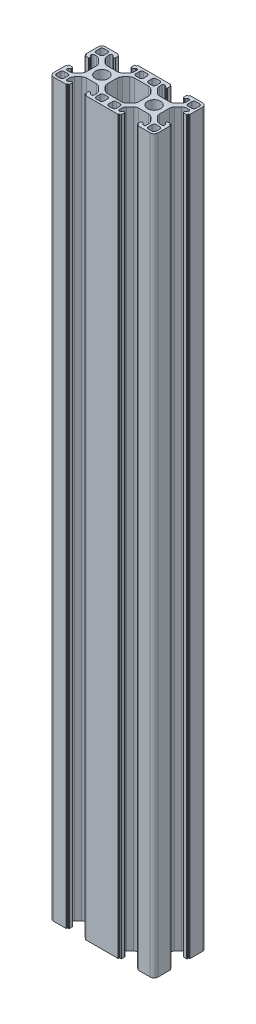
SolidWorks part; units mm, degrees
ref_plane "Спереди" through (0, 0, 0) normal (0, 0, 1) x (1, 0, 0)
ref_plane "Сверху" through (0, 0, 0) normal (0, 1, 0) x (1, 0, 0)
ref_plane "Справа" through (0, 0, 0) normal (1, 0, 0) x (0, 0, -1)
sketch "Эскиз1" plane through (0, 0, 0) normal (0, 1, 0) x (1, 0, 0)
  line L0 (-3.1522, 8.2837) -> (-1.6522, 6.7837) construction
  line L1 (18.3478, 9.7837) -> (15.3478, 6.7837) construction
  line L2 (-10.7522, 0.6837) -> (-0.7522, 10.6837) construction
  line L3 (9.2478, 4.6837) -> (11.1466, 4.6837)
  line L4 (9.2478, 0.6837) -> (19.2478, 10.6837) construction
  line L5 (16.8478, 8.2837) -> (15.3478, 9.7837) construction
  line L6 (12.5608, 5.2695) -> (13.862, 6.5707)
  line L7 (16.1478, 6.7837) -> (17.5478, 6.7837)
  line L8 (15.3478, 7.5837) -> (15.3478, 8.9837)
  line L9 (17.5478, 9.7837) -> (16.1478, 9.7837)
  line L10 (14.4478, 8.8837) -> (14.4478, 7.9849)
  line L11 (13.011, 8.757) -> (13.4914, 9.2373)
  line L12 (12.4478, 10.2328) -> (12.9478, 10.2328)
  line L13 (12.8343, 8.6837) -> (12.5478, 8.6837)
  line L14 (13.8449, 9.3837) -> (13.9478, 9.3837)
  line L15 (12.9478, 10.5337) -> (12.9478, 10.2328)
  line L16 (12.2978, 10.0828) -> (12.2978, 8.9337)
  line L17 (17.7478, 10.6837) -> (13.0978, 10.6837)
  line L18 (18.3478, 8.9837) -> (18.3478, 7.5837)
  line L19 (19.2478, 9.1837) -> (19.2478, 4.5337)
  line L20 (18.6469, 3.7337) -> (17.4978, 3.7337)
  line L21 (19.0978, 4.3837) -> (18.7969, 4.3837)
  line L22 (17.9478, 5.2808) -> (17.9478, 5.3837)
  line L23 (17.2478, 4.2702) -> (17.2478, 3.9837)
  line L24 (18.7969, 3.8837) -> (18.7969, 4.3837)
  line L25 (17.321, 4.447) -> (17.8014, 4.9273)
  line L26 (17.4478, 5.8837) -> (16.549, 5.8837)
  line L27 (13.8336, 3.9967) -> (15.1348, 5.2979)
  line L28 (13.2478, 0.6837) -> (13.2478, 2.5825)
  line L29 (13.2478, 0.6837) -> (13.2478, -1.2151)
  line L30 (13.8336, -2.6293) -> (15.1348, -3.9305)
  line L31 (15.3478, -6.2163) -> (15.3478, -7.6163)
  line L32 (16.1478, -5.4163) -> (17.5478, -5.4163)
  line L33 (18.3478, -7.6163) -> (18.3478, -6.2163)
  line L34 (17.4478, -4.5163) -> (16.549, -4.5163)
  line L35 (17.321, -3.0795) -> (17.8014, -3.5598)
  line L36 (18.7969, -2.5163) -> (18.7969, -3.0163)
  line L37 (17.2478, -2.9027) -> (17.2478, -2.6163)
  line L38 (17.9478, -3.9134) -> (17.9478, -4.0163)
  line L39 (19.0978, -3.0163) -> (18.7969, -3.0163)
  line L40 (18.6469, -2.3663) -> (17.4978, -2.3663)
  line L41 (19.2478, -7.8163) -> (19.2478, -3.1663)
  line L42 (17.5478, -8.4163) -> (16.1478, -8.4163)
  line L43 (17.7478, -9.3163) -> (13.0978, -9.3163)
  line L44 (12.2978, -8.7153) -> (12.2978, -7.5663)
  line L45 (12.9478, -9.1663) -> (12.9478, -8.8653)
  line L46 (13.8449, -8.0163) -> (13.9478, -8.0163)
  line L47 (12.8343, -7.3163) -> (12.5478, -7.3163)
  line L48 (12.4478, -8.8653) -> (12.9478, -8.8653)
  line L49 (13.011, -7.3895) -> (13.4914, -7.8698)
  line L50 (14.4478, -7.5163) -> (14.4478, -6.6175)
  line L51 (12.5608, -3.9021) -> (13.862, -5.2033)
  line L52 (9.2478, -3.3163) -> (11.1466, -3.3163)
  line L53 (18.3478, -8.4163) -> (15.3478, -5.4163) construction
  line L54 (9.2478, 0.6837) -> (19.2478, -9.3163) construction
  line L55 (16.8478, -6.9163) -> (18.3478, -5.4163) construction
  line L56 (9.2478, -3.3163) -> (7.349, -3.3163)
  line L57 (5.9348, -3.9021) -> (4.6336, -5.2033)
  line L58 (2.3478, -5.4163) -> (0.9478, -5.4163)
  line L59 (3.1478, -6.2163) -> (3.1478, -7.6163)
  line L60 (0.9478, -8.4163) -> (2.3478, -8.4163)
  line L61 (4.0478, -7.5163) -> (4.0478, -6.6175)
  line L62 (5.4846, -7.3895) -> (5.0043, -7.8698)
  line L63 (6.0478, -8.8653) -> (5.5478, -8.8653)
  line L64 (5.6614, -7.3163) -> (5.9478, -7.3163)
  line L65 (4.6507, -8.0163) -> (4.5478, -8.0163)
  line L66 (5.5478, -9.1663) -> (5.5478, -8.8653)
  line L67 (6.1978, -8.7153) -> (6.1978, -7.5663)
  line L68 (0.7478, -9.3163) -> (5.3978, -9.3163)
  line L69 (0.1478, -7.6163) -> (0.1478, -6.2163)
  line L70 (1.0478, -4.5163) -> (1.9466, -4.5163)
  line L71 (4.662, -2.6293) -> (3.3608, -3.9305)
  line L72 (5.2478, 0.6837) -> (5.2478, -1.2151)
  line L73 (-1.6522, 9.7837) -> (-4.6522, 6.7837) construction
  line L74 (0.1478, -8.4163) -> (3.1478, -5.4163) construction
  line L75 (-3.1522, -6.9163) -> (-4.6522, -8.4163) construction
  line L76 (9.2478, 0.6837) -> (-0.7522, -9.3163) construction
  line L77 (1.6478, -6.9163) -> (3.1478, -8.4163) construction
  line L78 (5.2478, 0.6837) -> (5.2478, 2.5825)
  line L79 (4.662, 3.9967) -> (3.3608, 5.2979)
  line L80 (3.1478, 7.5837) -> (3.1478, 8.9837)
  line L81 (2.3478, 6.7837) -> (0.9478, 6.7837)
  line L82 (0.1478, 8.9837) -> (0.1478, 7.5837)
  line L83 (1.0478, 5.8837) -> (1.9466, 5.8837)
  line L84 (0.9478, 9.7837) -> (2.3478, 9.7837)
  line L85 (0.7478, 10.6837) -> (5.3978, 10.6837)
  line L86 (6.1978, 10.0828) -> (6.1978, 8.9337)
  line L87 (5.5478, 10.5337) -> (5.5478, 10.2328)
  line L88 (4.6507, 9.3837) -> (4.5478, 9.3837)
  line L89 (5.6614, 8.6837) -> (5.9478, 8.6837)
  line L90 (6.0478, 10.2328) -> (5.5478, 10.2328)
  line L91 (5.4846, 8.757) -> (5.0043, 9.2373)
  line L92 (4.0478, 8.8837) -> (4.0478, 7.9849)
  line L93 (5.9348, 5.2695) -> (4.6336, 6.5707)
  line L94 (9.2478, 4.6837) -> (7.349, 4.6837)
  line L95 (-2.5162, 0.6837) -> (20.7522, 0.6837) construction
  line L96 (0.1478, 9.7837) -> (3.1478, 6.7837) construction
  line L97 (9.2478, -11.4027) -> (9.2478, 11.4027) construction
  line L98 (9.2478, 0.6837) -> (-0.7522, 10.6837) construction
  line L99 (1.6478, 8.2837) -> (0.1478, 6.7837) construction
  line L100 (-10.7522, 0.6837) -> (-0.7522, -9.3163) construction
  line L101 (-1.6522, -8.4163) -> (-4.6522, -5.4163) construction
  line L102 (-18.3522, -6.9163) -> (-19.8522, -5.4163) construction
  line L103 (-10.7522, 0.6837) -> (-20.7522, -9.3163) construction
  line L104 (-19.8522, -8.4163) -> (-16.8522, -5.4163) construction
  line L105 (-18.3522, 8.2837) -> (-16.8522, 9.7837) construction
  line L106 (-10.7522, 0.6837) -> (-20.7522, 10.6837) construction
  line L107 (-19.8522, 9.7837) -> (-16.8522, 6.7837) construction
  line L108 (-10.7522, 4.6837) -> (-8.8534, 4.6837)
  line L109 (-7.4392, 5.2695) -> (-6.138, 6.5707)
  line L110 (-5.5522, 8.8837) -> (-5.5522, 7.9849)
  line L111 (-6.989, 8.757) -> (-6.5086, 9.2373)
  line L112 (-7.5522, 10.2328) -> (-7.0522, 10.2328)
  line L113 (-7.1657, 8.6837) -> (-7.4522, 8.6837)
  line L114 (-6.1551, 9.3837) -> (-6.0522, 9.3837)
  line L115 (-7.0522, 10.5337) -> (-7.0522, 10.2328)
  line L116 (-7.7022, 10.0828) -> (-7.7022, 8.9337)
  line L117 (-2.2522, 10.6837) -> (-6.9022, 10.6837)
  line L118 (-2.4522, 9.7837) -> (-3.8522, 9.7837)
  line L119 (-2.5522, 5.8837) -> (-3.451, 5.8837)
  line L120 (-1.6522, 8.9837) -> (-1.6522, 7.5837)
  line L121 (-3.8522, 6.7837) -> (-2.4522, 6.7837)
  line L122 (-4.6522, 7.5837) -> (-4.6522, 8.9837)
  line L123 (-6.1664, 3.9967) -> (-4.8652, 5.2979)
  line L124 (-6.7522, 0.6837) -> (-6.7522, 2.5825)
  line L125 (-6.7522, 0.6837) -> (-6.7522, -1.2151)
  line L126 (-6.1664, -2.6293) -> (-4.8652, -3.9305)
  line L127 (-2.5522, -4.5163) -> (-3.451, -4.5163)
  line L128 (-1.6522, -7.6163) -> (-1.6522, -6.2163)
  line L129 (-2.2522, -9.3163) -> (-6.9022, -9.3163)
  line L130 (-7.7022, -8.7153) -> (-7.7022, -7.5663)
  line L131 (-7.0522, -9.1663) -> (-7.0522, -8.8653)
  line L132 (-6.1551, -8.0163) -> (-6.0522, -8.0163)
  line L133 (-7.1657, -7.3163) -> (-7.4522, -7.3163)
  line L134 (-7.5522, -8.8653) -> (-7.0522, -8.8653)
  line L135 (-6.989, -7.3895) -> (-6.5086, -7.8698)
  line L136 (-5.5522, -7.5163) -> (-5.5522, -6.6175)
  line L137 (-2.4522, -8.4163) -> (-3.8522, -8.4163)
  line L138 (-4.6522, -6.2163) -> (-4.6522, -7.6163)
  line L139 (-3.8522, -5.4163) -> (-2.4522, -5.4163)
  line L140 (-7.4392, -3.9021) -> (-6.138, -5.2033)
  line L141 (-10.7522, -3.3163) -> (-8.8534, -3.3163)
  line L142 (-10.7522, -3.3163) -> (-12.651, -3.3163)
  line L143 (-14.0652, -3.9021) -> (-15.3664, -5.2033)
  line L144 (-15.9522, -7.5163) -> (-15.9522, -6.6175)
  line L145 (-14.5154, -7.3895) -> (-14.9957, -7.8698)
  line L146 (-13.9522, -8.8653) -> (-14.4522, -8.8653)
  line L147 (-14.3386, -7.3163) -> (-14.0522, -7.3163)
  line L148 (-15.3493, -8.0163) -> (-15.4522, -8.0163)
  line L149 (-14.4522, -9.1663) -> (-14.4522, -8.8653)
  line L150 (-13.8022, -8.7153) -> (-13.8022, -7.5663)
  line L151 (-19.2522, -9.3163) -> (-14.6022, -9.3163)
  line L152 (-19.0522, -8.4163) -> (-17.6522, -8.4163)
  line L153 (-20.7522, -7.8163) -> (-20.7522, -3.1663)
  line L154 (-20.1512, -2.3663) -> (-19.0022, -2.3663)
  line L155 (-20.6022, -3.0163) -> (-20.3012, -3.0163)
  line L156 (-19.4522, -3.9134) -> (-19.4522, -4.0163)
  line L157 (-18.7522, -2.9027) -> (-18.7522, -2.6163)
  line L158 (-20.3012, -2.5163) -> (-20.3012, -3.0163)
  line L159 (-18.8254, -3.0795) -> (-19.3057, -3.5598)
  line L160 (-18.9522, -4.5163) -> (-18.0534, -4.5163)
  line L161 (-19.8522, -7.6163) -> (-19.8522, -6.2163)
  line L162 (-17.6522, -5.4163) -> (-19.0522, -5.4163)
  line L163 (-16.8522, -6.2163) -> (-16.8522, -7.6163)
  line L164 (-15.338, -2.6293) -> (-16.6392, -3.9305)
  line L165 (-14.7522, 0.6837) -> (-14.7522, -1.2151)
  line L166 (-14.7522, 0.6837) -> (-14.7522, 2.5825)
  line L167 (-15.338, 3.9967) -> (-16.6392, 5.2979)
  line L168 (-18.9522, 5.8837) -> (-18.0534, 5.8837)
  line L169 (-18.8254, 4.447) -> (-19.3057, 4.9273)
  line L170 (-20.3012, 3.8837) -> (-20.3012, 4.3837)
  line L171 (-18.7522, 4.2702) -> (-18.7522, 3.9837)
  line L172 (-19.4522, 5.2808) -> (-19.4522, 5.3837)
  line L173 (-20.6022, 4.3837) -> (-20.3012, 4.3837)
  line L174 (-20.1512, 3.7337) -> (-19.0022, 3.7337)
  line L175 (-20.7522, 9.1837) -> (-20.7522, 4.5337)
  line L176 (-19.8522, 8.9837) -> (-19.8522, 7.5837)
  line L177 (-19.2522, 10.6837) -> (-14.6022, 10.6837)
  line L178 (-13.8022, 10.0828) -> (-13.8022, 8.9337)
  line L179 (-14.4522, 10.5337) -> (-14.4522, 10.2328)
  line L180 (-15.3493, 9.3837) -> (-15.4522, 9.3837)
  line L181 (-14.3386, 8.6837) -> (-14.0522, 8.6837)
  line L182 (-13.9522, 10.2328) -> (-14.4522, 10.2328)
  line L183 (-14.5154, 8.757) -> (-14.9957, 9.2373)
  line L184 (-15.9522, 8.8837) -> (-15.9522, 7.9849)
  line L185 (-19.0522, 9.7837) -> (-17.6522, 9.7837)
  line L186 (-16.8522, 7.5837) -> (-16.8522, 8.9837)
  line L187 (-17.6522, 6.7837) -> (-19.0522, 6.7837)
  line L188 (-14.0652, 5.2695) -> (-15.3664, 6.5707)
  line L189 (-10.7522, 4.6837) -> (-12.651, 4.6837)
  line L190 (-2.2522, -9.3163) -> (0.7478, -9.3163)
  line L191 (-2.5522, -4.5163) -> (1.0478, -4.5163)
  line L192 (-2.5522, 5.8837) -> (1.0478, 5.8837)
  line L193 (-2.2522, 10.6837) -> (0.7478, 10.6837)
  arc A0 (18.3478, 8.9837) -> (17.5478, 9.7837) centre (17.5478, 8.9837) ccw
  arc A1 (16.1478, 9.7837) -> (15.3478, 8.9837) centre (16.1478, 8.9837) ccw
  arc A2 (16.1478, 6.7837) -> (15.3478, 7.5837) centre (16.1478, 7.5837) cw
  arc A3 (17.7478, 10.6837) -> (19.2478, 9.1837) centre (17.7478, 9.1837) cw
  arc A4 (12.4478, 10.2328) -> (12.2978, 10.0828) centre (12.4478, 10.0828) ccw
  arc A5 (13.0978, 10.6837) -> (12.9478, 10.5337) centre (13.0978, 10.5337) ccw
  arc A6 (12.8343, 8.6837) -> (13.011, 8.757) centre (12.8343, 8.9337) ccw
  arc A7 (12.5478, 8.6837) -> (12.2978, 8.9337) centre (12.5478, 8.9337) cw
  arc A8 (13.4914, 9.2373) -> (13.8449, 9.3837) centre (13.8449, 8.8837) cw
  arc A9 (13.9478, 9.3837) -> (14.4478, 8.8837) centre (13.9478, 8.8837) cw
  arc A10 (11.7478, 0.6837) -> (9.2478, 3.1837) centre (9.2478, 0.6837) ccw
  arc A11 (11.1466, 4.6837) -> (12.5608, 5.2695) centre (11.1466, 6.6837) ccw
  arc A12 (14.4478, 7.9849) -> (13.862, 6.5707) centre (12.4478, 7.9849) cw
  arc A13 (18.3478, 7.5837) -> (17.5478, 6.7837) centre (17.5478, 7.5837) cw
  arc A14 (17.9478, 5.3837) -> (17.4478, 5.8837) centre (17.4478, 5.3837) ccw
  arc A15 (17.8014, 4.9273) -> (17.9478, 5.2808) centre (17.4478, 5.2808) ccw
  arc A16 (17.2478, 3.9837) -> (17.4978, 3.7337) centre (17.4978, 3.9837) ccw
  arc A17 (17.2478, 4.2702) -> (17.321, 4.447) centre (17.4978, 4.2702) cw
  arc A18 (19.2478, 4.5337) -> (19.0978, 4.3837) centre (19.0978, 4.5337) cw
  arc A19 (18.7969, 3.8837) -> (18.6469, 3.7337) centre (18.6469, 3.8837) cw
  arc A20 (16.549, 5.8837) -> (15.1348, 5.2979) centre (16.549, 3.8837) ccw
  arc A21 (13.2478, 2.5825) -> (13.8336, 3.9967) centre (15.2478, 2.5825) cw
  arc A22 (17.5478, -8.4163) -> (18.3478, -7.6163) centre (17.5478, -7.6163) ccw
  arc A23 (18.3478, -6.2163) -> (17.5478, -5.4163) centre (17.5478, -6.2163) ccw
  arc A24 (15.3478, -6.2163) -> (16.1478, -5.4163) centre (16.1478, -6.2163) cw
  arc A25 (19.2478, -7.8163) -> (17.7478, -9.3163) centre (17.7478, -7.8163) cw
  arc A26 (18.7969, -2.5163) -> (18.6469, -2.3663) centre (18.6469, -2.5163) ccw
  arc A27 (19.2478, -3.1663) -> (19.0978, -3.0163) centre (19.0978, -3.1663) ccw
  arc A28 (17.2478, -2.9027) -> (17.321, -3.0795) centre (17.4978, -2.9027) ccw
  arc A29 (17.2478, -2.6163) -> (17.4978, -2.3663) centre (17.4978, -2.6163) cw
  arc A30 (17.8014, -3.5598) -> (17.9478, -3.9134) centre (17.4478, -3.9134) cw
  arc A31 (17.9478, -4.0163) -> (17.4478, -4.5163) centre (17.4478, -4.0163) cw
  arc A32 (9.2478, -1.8163) -> (11.7478, 0.6837) centre (9.2478, 0.6837) ccw
  arc A33 (13.2478, -1.2151) -> (13.8336, -2.6293) centre (15.2478, -1.2151) ccw
  arc A34 (16.549, -4.5163) -> (15.1348, -3.9305) centre (16.549, -2.5163) cw
  arc A35 (16.1478, -8.4163) -> (15.3478, -7.6163) centre (16.1478, -7.6163) cw
  arc A36 (13.9478, -8.0163) -> (14.4478, -7.5163) centre (13.9478, -7.5163) ccw
  arc A37 (13.4914, -7.8698) -> (13.8449, -8.0163) centre (13.8449, -7.5163) ccw
  arc A38 (12.5478, -7.3163) -> (12.2978, -7.5663) centre (12.5478, -7.5663) ccw
  arc A39 (12.8343, -7.3163) -> (13.011, -7.3895) centre (12.8343, -7.5663) cw
  arc A40 (13.0978, -9.3163) -> (12.9478, -9.1663) centre (13.0978, -9.1663) cw
  arc A41 (12.4478, -8.8653) -> (12.2978, -8.7153) centre (12.4478, -8.7153) cw
  arc A42 (14.4478, -6.6175) -> (13.862, -5.2033) centre (12.4478, -6.6175) ccw
  arc A43 (11.1466, -3.3163) -> (12.5608, -3.9021) centre (11.1466, -5.3163) cw
  arc A44 (0.1478, -7.6163) -> (0.9478, -8.4163) centre (0.9478, -7.6163) ccw
  arc A45 (2.3478, -8.4163) -> (3.1478, -7.6163) centre (2.3478, -7.6163) ccw
  arc A46 (2.3478, -5.4163) -> (3.1478, -6.2163) centre (2.3478, -6.2163) cw
  arc A47 (6.0478, -8.8653) -> (6.1978, -8.7153) centre (6.0478, -8.7153) ccw
  arc A48 (5.3978, -9.3163) -> (5.5478, -9.1663) centre (5.3978, -9.1663) ccw
  arc A49 (5.6614, -7.3163) -> (5.4846, -7.3895) centre (5.6614, -7.5663) ccw
  arc A50 (5.9478, -7.3163) -> (6.1978, -7.5663) centre (5.9478, -7.5663) cw
  arc A51 (5.0043, -7.8698) -> (4.6507, -8.0163) centre (4.6507, -7.5163) cw
  arc A52 (4.5478, -8.0163) -> (4.0478, -7.5163) centre (4.5478, -7.5163) cw
  arc A53 (6.7478, 0.6837) -> (9.2478, -1.8163) centre (9.2478, 0.6837) ccw
  arc A54 (7.349, -3.3163) -> (5.9348, -3.9021) centre (7.349, -5.3163) ccw
  arc A55 (4.0478, -6.6175) -> (4.6336, -5.2033) centre (6.0478, -6.6175) cw
  arc A56 (0.1478, -6.2163) -> (0.9478, -5.4163) centre (0.9478, -6.2163) cw
  arc A57 (1.9466, -4.5163) -> (3.3608, -3.9305) centre (1.9466, -2.5163) ccw
  arc A58 (5.2478, -1.2151) -> (4.662, -2.6293) centre (3.2478, -1.2151) cw
  arc A59 (0.9478, 9.7837) -> (0.1478, 8.9837) centre (0.9478, 8.9837) ccw
  arc A60 (0.1478, 7.5837) -> (0.9478, 6.7837) centre (0.9478, 7.5837) ccw
  arc A61 (3.1478, 7.5837) -> (2.3478, 6.7837) centre (2.3478, 7.5837) cw
  arc A62 (9.2478, 3.1837) -> (6.7478, 0.6837) centre (9.2478, 0.6837) ccw
  arc A63 (5.2478, 2.5825) -> (4.662, 3.9967) centre (3.2478, 2.5825) ccw
  arc A64 (1.9466, 5.8837) -> (3.3608, 5.2979) centre (1.9466, 3.8837) cw
  arc A65 (2.3478, 9.7837) -> (3.1478, 8.9837) centre (2.3478, 8.9837) cw
  arc A66 (4.5478, 9.3837) -> (4.0478, 8.8837) centre (4.5478, 8.8837) ccw
  arc A67 (5.0043, 9.2373) -> (4.6507, 9.3837) centre (4.6507, 8.8837) ccw
  arc A68 (5.9478, 8.6837) -> (6.1978, 8.9337) centre (5.9478, 8.9337) ccw
  arc A69 (5.6614, 8.6837) -> (5.4846, 8.757) centre (5.6614, 8.9337) cw
  arc A70 (5.3978, 10.6837) -> (5.5478, 10.5337) centre (5.3978, 10.5337) cw
  arc A71 (6.0478, 10.2328) -> (6.1978, 10.0828) centre (6.0478, 10.0828) cw
  arc A72 (4.0478, 7.9849) -> (4.6336, 6.5707) centre (6.0478, 7.9849) ccw
  arc A73 (7.349, 4.6837) -> (5.9348, 5.2695) centre (7.349, 6.6837) cw
  arc A74 (-8.8534, 4.6837) -> (-7.4392, 5.2695) centre (-8.8534, 6.6837) ccw
  arc A75 (-5.5522, 7.9849) -> (-6.138, 6.5707) centre (-7.5522, 7.9849) cw
  arc A76 (-7.5522, 10.2328) -> (-7.7022, 10.0828) centre (-7.5522, 10.0828) ccw
  arc A77 (-6.9022, 10.6837) -> (-7.0522, 10.5337) centre (-6.9022, 10.5337) ccw
  arc A78 (-7.1657, 8.6837) -> (-6.989, 8.757) centre (-7.1657, 8.9337) ccw
  arc A79 (-7.4522, 8.6837) -> (-7.7022, 8.9337) centre (-7.4522, 8.9337) cw
  arc A80 (-6.5086, 9.2373) -> (-6.1551, 9.3837) centre (-6.1551, 8.8837) cw
  arc A81 (-6.0522, 9.3837) -> (-5.5522, 8.8837) centre (-6.0522, 8.8837) cw
  arc A82 (-3.8522, 9.7837) -> (-4.6522, 8.9837) centre (-3.8522, 8.9837) ccw
  arc A83 (-3.451, 5.8837) -> (-4.8652, 5.2979) centre (-3.451, 3.8837) ccw
  arc A84 (-6.7522, 2.5825) -> (-6.1664, 3.9967) centre (-4.7522, 2.5825) cw
  arc A85 (-10.7522, 3.1837) -> (-8.2522, 0.6837) centre (-10.7522, 0.6837) cw
  arc A86 (-4.6522, 7.5837) -> (-3.8522, 6.7837) centre (-3.8522, 7.5837) ccw
  arc A87 (-1.6522, 7.5837) -> (-2.4522, 6.7837) centre (-2.4522, 7.5837) cw
  arc A88 (-2.4522, 9.7837) -> (-1.6522, 8.9837) centre (-2.4522, 8.9837) cw
  arc A89 (-6.7522, -1.2151) -> (-6.1664, -2.6293) centre (-4.7522, -1.2151) ccw
  arc A90 (-3.451, -4.5163) -> (-4.8652, -3.9305) centre (-3.451, -2.5163) cw
  arc A91 (-1.6522, -6.2163) -> (-2.4522, -5.4163) centre (-2.4522, -6.2163) ccw
  arc A92 (-5.5522, -6.6175) -> (-6.138, -5.2033) centre (-7.5522, -6.6175) ccw
  arc A93 (-8.8534, -3.3163) -> (-7.4392, -3.9021) centre (-8.8534, -5.3163) cw
  arc A94 (-8.2522, 0.6837) -> (-10.7522, -1.8163) centre (-10.7522, 0.6837) cw
  arc A95 (-6.0522, -8.0163) -> (-5.5522, -7.5163) centre (-6.0522, -7.5163) ccw
  arc A96 (-6.5086, -7.8698) -> (-6.1551, -8.0163) centre (-6.1551, -7.5163) ccw
  arc A97 (-7.4522, -7.3163) -> (-7.7022, -7.5663) centre (-7.4522, -7.5663) ccw
  arc A98 (-7.1657, -7.3163) -> (-6.989, -7.3895) centre (-7.1657, -7.5663) cw
  arc A99 (-6.9022, -9.3163) -> (-7.0522, -9.1663) centre (-6.9022, -9.1663) cw
  arc A100 (-7.5522, -8.8653) -> (-7.7022, -8.7153) centre (-7.5522, -8.7153) cw
  arc A101 (-3.8522, -5.4163) -> (-4.6522, -6.2163) centre (-3.8522, -6.2163) ccw
  arc A102 (-3.8522, -8.4163) -> (-4.6522, -7.6163) centre (-3.8522, -7.6163) cw
  arc A103 (-1.6522, -7.6163) -> (-2.4522, -8.4163) centre (-2.4522, -7.6163) cw
  arc A104 (-12.651, -3.3163) -> (-14.0652, -3.9021) centre (-12.651, -5.3163) ccw
  arc A105 (-15.9522, -6.6175) -> (-15.3664, -5.2033) centre (-13.9522, -6.6175) cw
  arc A106 (-13.9522, -8.8653) -> (-13.8022, -8.7153) centre (-13.9522, -8.7153) ccw
  arc A107 (-14.6022, -9.3163) -> (-14.4522, -9.1663) centre (-14.6022, -9.1663) ccw
  arc A108 (-14.3386, -7.3163) -> (-14.5154, -7.3895) centre (-14.3386, -7.5663) ccw
  arc A109 (-14.0522, -7.3163) -> (-13.8022, -7.5663) centre (-14.0522, -7.5663) cw
  arc A110 (-14.9957, -7.8698) -> (-15.3493, -8.0163) centre (-15.3493, -7.5163) cw
  arc A111 (-15.4522, -8.0163) -> (-15.9522, -7.5163) centre (-15.4522, -7.5163) cw
  arc A112 (-17.6522, -8.4163) -> (-16.8522, -7.6163) centre (-17.6522, -7.6163) ccw
  arc A113 (-18.0534, -4.5163) -> (-16.6392, -3.9305) centre (-18.0534, -2.5163) ccw
  arc A114 (-14.7522, -1.2151) -> (-15.338, -2.6293) centre (-16.7522, -1.2151) cw
  arc A115 (-10.7522, -1.8163) -> (-13.2522, 0.6837) centre (-10.7522, 0.6837) cw
  arc A116 (-19.4522, -4.0163) -> (-18.9522, -4.5163) centre (-18.9522, -4.0163) ccw
  arc A117 (-19.3057, -3.5598) -> (-19.4522, -3.9134) centre (-18.9522, -3.9134) ccw
  arc A118 (-18.7522, -2.6163) -> (-19.0022, -2.3663) centre (-19.0022, -2.6163) ccw
  arc A119 (-18.7522, -2.9027) -> (-18.8254, -3.0795) centre (-19.0022, -2.9027) cw
  arc A120 (-20.7522, -3.1663) -> (-20.6022, -3.0163) centre (-20.6022, -3.1663) cw
  arc A121 (-20.3012, -2.5163) -> (-20.1512, -2.3663) centre (-20.1512, -2.5163) cw
  arc A122 (-20.7522, -7.8163) -> (-19.2522, -9.3163) centre (-19.2522, -7.8163) ccw
  arc A123 (-16.8522, -6.2163) -> (-17.6522, -5.4163) centre (-17.6522, -6.2163) ccw
  arc A124 (-19.8522, -6.2163) -> (-19.0522, -5.4163) centre (-19.0522, -6.2163) cw
  arc A125 (-19.0522, -8.4163) -> (-19.8522, -7.6163) centre (-19.0522, -7.6163) cw
  arc A126 (-14.7522, 2.5825) -> (-15.338, 3.9967) centre (-16.7522, 2.5825) ccw
  arc A127 (-18.0534, 5.8837) -> (-16.6392, 5.2979) centre (-18.0534, 3.8837) cw
  arc A128 (-20.3012, 3.8837) -> (-20.1512, 3.7337) centre (-20.1512, 3.8837) ccw
  arc A129 (-20.7522, 4.5337) -> (-20.6022, 4.3837) centre (-20.6022, 4.5337) ccw
  arc A130 (-18.7522, 4.2702) -> (-18.8254, 4.447) centre (-19.0022, 4.2702) ccw
  arc A131 (-18.7522, 3.9837) -> (-19.0022, 3.7337) centre (-19.0022, 3.9837) cw
  arc A132 (-19.3057, 4.9273) -> (-19.4522, 5.2808) centre (-18.9522, 5.2808) cw
  arc A133 (-19.4522, 5.3837) -> (-18.9522, 5.8837) centre (-18.9522, 5.3837) cw
  arc A134 (-19.8522, 7.5837) -> (-19.0522, 6.7837) centre (-19.0522, 7.5837) ccw
  arc A135 (-15.9522, 7.9849) -> (-15.3664, 6.5707) centre (-13.9522, 7.9849) ccw
  arc A136 (-12.651, 4.6837) -> (-14.0652, 5.2695) centre (-12.651, 6.6837) cw
  arc A137 (-13.2522, 0.6837) -> (-10.7522, 3.1837) centre (-10.7522, 0.6837) cw
  arc A138 (-15.4522, 9.3837) -> (-15.9522, 8.8837) centre (-15.4522, 8.8837) ccw
  arc A139 (-14.9957, 9.2373) -> (-15.3493, 9.3837) centre (-15.3493, 8.8837) ccw
  arc A140 (-14.0522, 8.6837) -> (-13.8022, 8.9337) centre (-14.0522, 8.9337) ccw
  arc A141 (-14.3386, 8.6837) -> (-14.5154, 8.757) centre (-14.3386, 8.9337) cw
  arc A142 (-14.6022, 10.6837) -> (-14.4522, 10.5337) centre (-14.6022, 10.5337) cw
  arc A143 (-13.9522, 10.2328) -> (-13.8022, 10.0828) centre (-13.9522, 10.0828) cw
  arc A144 (-19.2522, 10.6837) -> (-20.7522, 9.1837) centre (-19.2522, 9.1837) ccw
  arc A145 (-17.6522, 6.7837) -> (-16.8522, 7.5837) centre (-17.6522, 7.5837) ccw
  arc A146 (-17.6522, 9.7837) -> (-16.8522, 8.9837) centre (-17.6522, 8.9837) cw
  arc A147 (-19.8522, 8.9837) -> (-19.0522, 9.7837) centre (-19.0522, 8.9837) cw
  point P0 (9.2478, 0.6837)
  point P12 (9.2478, 0.6837)
  point P45 (17.9478, 4.3837)
  point P104 (12.9478, -8.0163)
  point P155 (12.9478, 9.3837)
  point P163 (17.9478, -3.0163)
  point P164 (9.2478, -3.2405)
  point P166 (9.2478, 0.6837)
  point P224 (5.5478, -8.0163)
  point P225 (5.3236, 0.6837)
  point P227 (9.2478, 0.6837)
  point P267 (5.5478, 9.3837)
  point P272 (13.1721, 0.6837)
  point P288 (9.2478, 4.608)
  point P290 (9.2478, 0.6837)
  point P515 (-10.7522, 4.608)
  point P516 (-14.6764, 0.6837)
  point P517 (-7.0522, 9.3837)
  point P518 (-6.8279, 0.6837)
  point P519 (-7.0522, -8.0163)
  point P520 (-10.7522, -3.2405)
  point P521 (-19.4522, -3.0163)
  point P522 (-14.4522, 9.3837)
  point P523 (-14.4522, -8.0163)
  point P524 (-19.4522, 4.3837)
extrude "Бобышка-Вытянуть1" add sketch "Эскиз1" along normal blind 280
